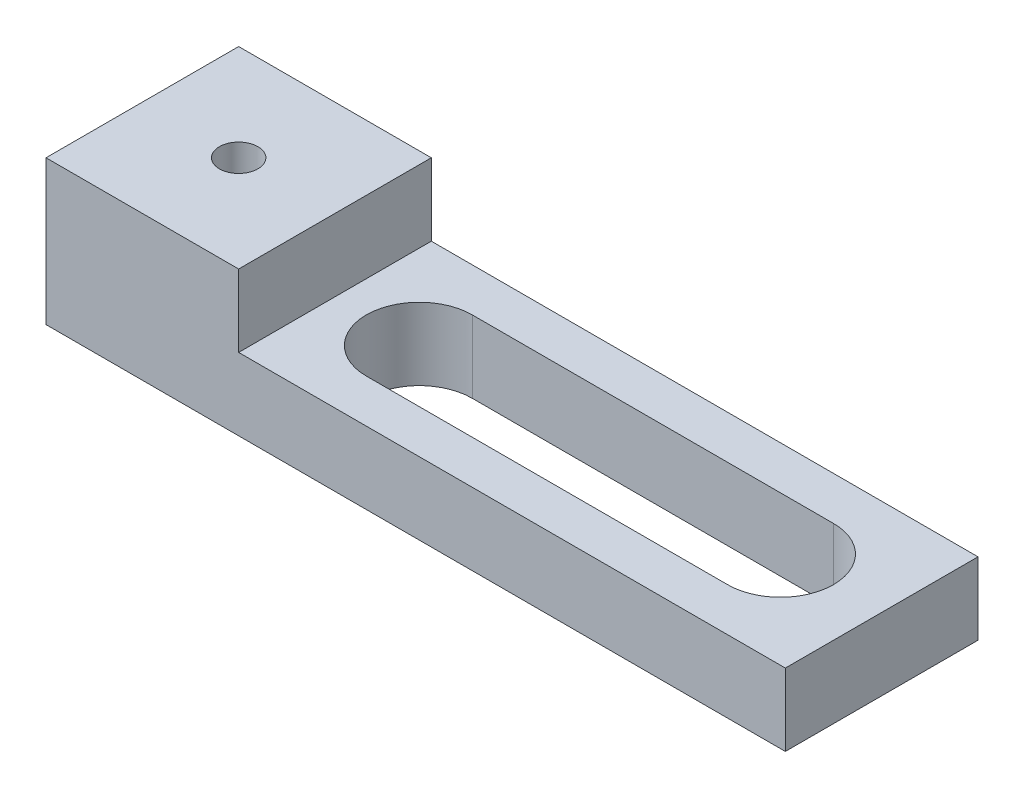
SolidWorks part; units mm, degrees
ref_plane "Front Plane" through (0, 0, 0) normal (0, 0, 1) x (1, 0, 0)
ref_plane "Top Plane" through (0, 0, 0) normal (0, 1, 0) x (1, 0, 0)
ref_plane "Right Plane" through (0, 0, 0) normal (1, 0, 0) x (0, 0, -1)
sketch "Sketch1" plane through (0, 0, 0) normal (0, 1, 0) x (1, 0, 0)
  line L0 (0, 0) -> (15, 0) construction
  line L1 (0, 2.2) -> (15, 2.2)
  line L2 (0, -2.2) -> (15, -2.2)
  line L4 (19.2, 4) -> (-11.5, 4)
  line L5 (19.2, 4) -> (19.2, -4)
  line L6 (19.2, -4) -> (-11.5, -4)
  line L7 (-11.5, 4) -> (-11.5, -4)
  arc A0 (0, 2.2) -> (0, -2.2) centre (0, 0) ccw
  arc A1 (15, -2.2) -> (15, 2.2) centre (15, 0) ccw
  circle A2 centre (0, 0) radius 3.5 construction
  point P3 (7.5, 0)
  point P12 (-11.5, 0)
  point P13 (17.2, 0)
  point P14 (-2.2, 0)
  point P17 (-3.5, 0)
  dimension "D6" = 7
  dimension "D1" = 15
  dimension "D2" = 4.4
  dimension "D3" = 8
  dimension "D4" = 2
  dimension "D5" = 8
extrude "Boss-Extrude1" add sketch "Sketch1" along normal blind 3
sketch "Sketch2" plane through (0, 3, 0) normal (0, 1, 0) x (1, 0, 0)
  line L0 (-11.5, -4) -> (19.2, -4) construction
  line L1 (-11.5, 4) -> (-3.5, 4)
  line L2 (-11.5, 4) -> (-11.5, -4)
  line L3 (-11.5, -4) -> (-3.5, -4)
  line L4 (-3.5, 4) -> (-3.5, -4)
  dimension "D1" = 8
extrude "Boss-Extrude2" add sketch "Sketch2" along normal blind 3
sketch "Sketch3" plane through (0, 6, 0) normal (0, 1, 0) x (1, 0, 0)
  line L2 (-11.5, 4) -> (-3.5, -4) construction
  line L3 (-11.5, -4) -> (-3.5, 4) construction
  circle A0 centre (-7.5, 0) radius 0.8
  dimension "D1" = 1.6
extrude "Cut-Extrude1" cut sketch "Sketch3" against normal up to next
equation "\"Mounting screw tap drill\"=1.6"
equation "\"D1@Sketch3\"=\"Mounting screw tap drill\""
